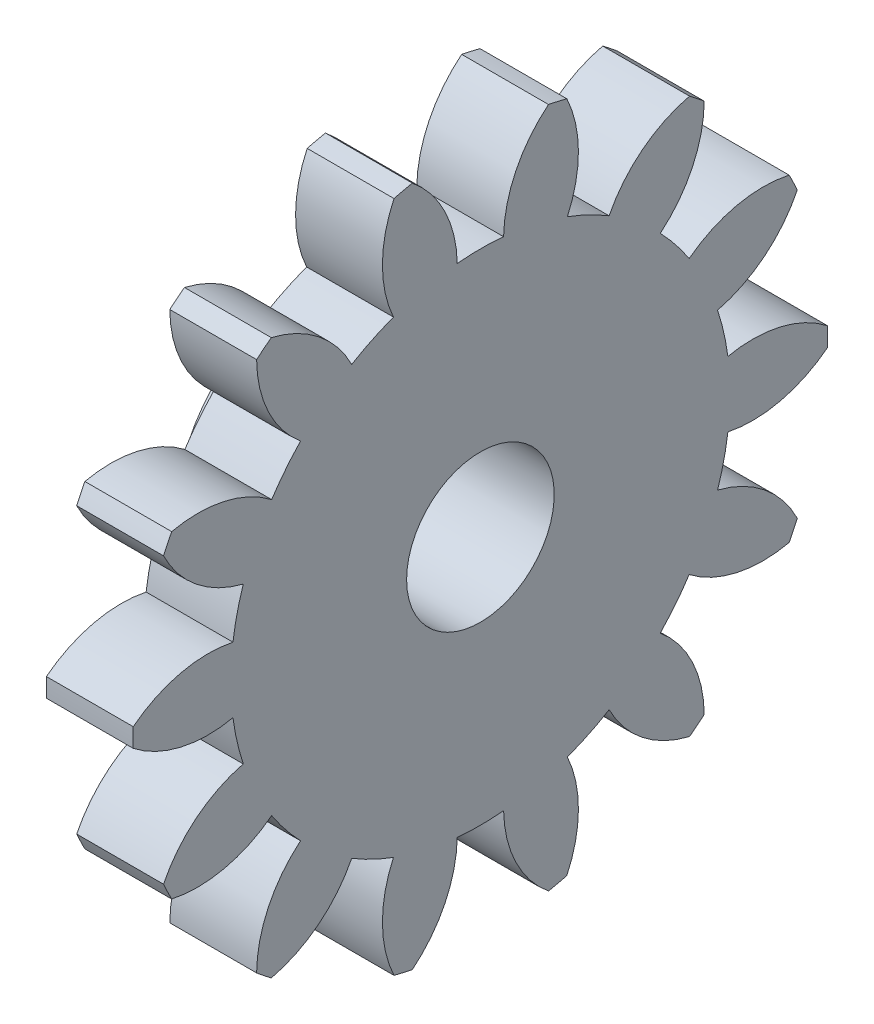
SolidWorks part; units mm, degrees
ref_plane "Plane1" through (0, 0, 0) normal (0, 0, 1) x (1, 0, 0)
ref_plane "Plane2" through (0, 0, 0) normal (0, 1, 0) x (1, 0, 0)
ref_plane "Plane3" through (0, 0, 0) normal (1, 0, 0) x (0, 0, -1)
sketch "HoldingSke" plane through (0, 0, 0) normal (0, 1, 0) x (1, 0, 0)
  line L0 (0, 0) -> (0.1941, -0.0484)
  line L1 (-15, 0) -> (100, 0) construction
  line L2 (0, 0) -> (-2.1039, 2.3779)
  line L3 (0, 0) -> (-11.863, 4.5341)
  line L4 (0, 0) -> (8.3795, 2.0892)
  line L5 (0, 0) -> (-18.7391, -6.9891)
  line L6 (0, 0) -> (-8.2896, -5.593)
  line L7 (-2.1039, 2.3779) -> (2.2011, 21.9091)
  line L8 (-76.2, 54.61) -> (-73.4, 54.61)
  line L9 (-71.009, 38.7566) -> (-53.1078, 45.2721)
  line L10 (-76.2, 71.12) -> (104.1128, 71.12)
  line L11 (0, 0) -> (-10, 0)
  line L12 (-76.2, 101.6) -> (-76.033, 101.6)
  line L13 (24.9733, 27.94) -> (52.9518, 28.4284)
  line L14 (24.9733, 27.94) -> (24.9743, 27.94)
  line L15 (24.9733, 27.94) -> (100.4006, 29.5858)
  line L16 (-63.627, -5) -> (-12.827, -5)
  circle A0 centre (0, 0) radius 8.5
  circle A1 centre (0, 0) radius 15
  circle A2 centre (0, 0) radius 15
  circle A3 centre (0, 0) radius 8.5
  dimension "MHD" = 30
  dimension "Hub_dia" = 30
  dimension "Bore" = 17
  dimension "MBD" = 17
  dimension "Num_teeth" = 14
  dimension "Pitch" = 0.2
  dimension "Overall_len" = 20
  dimension "Show_teeth" = 14
  dimension "Thickness" = 10
  dimension "OAL" = 20.0001
  dimension "T_dim" = 2.8
  dimension "Ap" = 20
  dimension "H" = 19.05
  dimension "Pitch_radius" = 180.3128
  dimension "Width" = 10
  dimension "Backlash" = 0.167
  dimension "Addendum_fac" = 1
  dimension "Dedendum_fac" = 1.25
  dimension "Clearance_fac" = 0.25
  dimension "Dedendum_add" = 0.001
  dimension "Module" = 5
sketch "BasProSke" plane through (0, 0, 0) normal (0, 1, 0) x (1, 0, 0)
  line L0 (-10, 0) -> (60, 0) construction
  line L1 (0, 0) -> (0, 40)
  line L2 (0, 0) -> (10, 0)
  line L3 (10, 0) -> (10, 40)
  line L4 (10, 40) -> (0, 40)
  dimension "Thickness" = 10
  dimension "Diameter" = 80
revolve "Base-Revolve" add sketch "BasProSke" angle 360 about L0
sketch "TooCutSke" plane through (0, 0, 0) normal (1, 0, 0) x (0, 0, -1)
  line L1 (0, 0) -> (0, 107) construction
  line L2 (0, 0) -> (-4.2107, 34.7458) construction
  line L3 (0, 0) -> (-15.4926, 67.8776) construction
  line L4 (-4.2107, 34.7458) -> (-7.7463, 33.9388) construction
  arc A0 (2.669, 28.6248) -> (-2.669, 28.6248) centre (0, 0) ccw
  arc A1 (7.8688, 39.2443) -> (-7.8688, 39.2443) centre (0, 0) ccw
  circle A2 centre (0, 0) radius 35 construction
  circle A3 centre (0, 0) radius 32.8892 construction
  arc A4 (-2.669, 28.6248) -> (-7.8688, 39.2443) centre (-16.6663, 28.3538) ccw
  arc A5 (7.8688, 39.2443) -> (2.669, 28.6248) centre (16.6663, 28.3538) ccw
  dimension "Root_dia" = 57.498
  dimension "Overcut_dia" = 80.0508
  dimension "Pitch_dia" = 70
  dimension "Base_dia" = 65.7785
  dimension "Flank_rad" = 14
  dimension "Half_ang" = 12.857
  dimension "Half_CT" = 3.6265
extrude "ToothCut" cut sketch "TooCutSke" along normal through all
fillet "Breaks" [suppressed] radius 0.1
fillet "RootFillets" [suppressed] radius 1.251
pattern_circular "TeethCuts" count 14 over 360 about axis through (0, 0, 0) along (1, 0, 0) of "ToothCut", "RootFillets", "Breaks"
sketch "HubNeaOneSke" plane through (0, 0, 0) normal (-1, 0, 0) x (0, 0, 1)
  circle A0 centre (0, 0) radius 15
  dimension "Diameter" = 30
extrude "HubNearOne" add sketch "HubNeaOneSke" along normal blind 10.0001
sketch "HubNeaBotSke" plane through (0, 0, 0) normal (-1, 0, 0) x (0, 0, 1)
  circle A0 centre (0, 0) radius 15
  dimension "Diameter" = 30
extrude "HubNearBoth" [suppressed] add sketch "HubNeaBotSke" along normal blind 5
ref_plane "FarPln" through (10, 0, 0) normal (1, 0, 0) x (0, 0, -1)
sketch "HubFarSke" plane through (10, 0, 0) normal (1, 0, 0) x (0, 0, -1)
  circle A0 centre (0, 0) radius 15
  dimension "Diameter" = 30
extrude "HubFar" [suppressed] add sketch "HubFarSke" along normal blind 5
sketch "BorSke" plane through (0, 0, 0) normal (1, 0, 0) x (0, 0, -1)
  circle A0 centre (0, 0) radius 8.5
  dimension "Diameter" = 17
extrude "Bore" cut sketch "BorSke" along normal mid plane 40.0001
sketch "KeySke" plane through (0, 0, 0) normal (1, 0, 0) x (0, 0, -1)
  line L0 (-3, 0) -> (-3, 11.3)
  line L1 (-3, 11.3) -> (3, 11.3)
  line L2 (3, 11.3) -> (3, 0)
  line L3 (0, 0) -> (0, 34) construction
  line L4 (-3, 0) -> (3, 0)
  dimension "Offset" = 11.3
  dimension "Width" = 6
extrude "Keyway" [suppressed] cut sketch "KeySke" along normal mid plane 40.0001
pattern_circular "Keyway2" [suppressed] count 2 every 90 about axis through (-10, 0, 0) along (1, 0, 0)
sketch "Sketch1" plane through (0, 0, 0) normal (0, 1, 0) x (1, 0, 0)
  line L0 (-10.0001, 15) -> (-10.0001, -15) construction
  circle A0 centre (-5.0001, 0) radius 1.75
  dimension "D1" = 5
extrude "Cut-Extrude1" cut sketch "Sketch1" against normal through all both and the other way through all
equation "' \"Module@HoldingSke\" = 6.35"
equation "' \"Num_teeth@HoldingSke\" = 12"
equation "' \"Ap@HoldingSke\" =  20"
equation "' \"Ap@HoldingSke\" = 20"
equation "' \"Width@HoldingSke\" = 0.5 * 25.4"
equation "' \"Hub_dia@HoldingSke\"= 1 * 25.4"
equation "' \"Hub_dia@HoldingSke\" = 1 * 25.4"
equation "' \"Overall_len@HoldingSke\" = 1.0 * 25.4"
equation "' \"Bore@HoldingSke\" = 0.75 * 25.4"
equation "' \"T_dim@HoldingSke\" = 0.1 * 25.4"
equation "' \"Width@KeySke\" = 0.25 * 25.4"
equation "' \"Show_teeth@HoldingSke\" = 13"
equation "' \"Backlash@HoldingSke\" = 0.009 * 25.4"
equation "' \"Addendum_fac@HoldingSke\" = 1.0"
equation "' \"Dedendum_fac@HoldingSke\" = 1.25"
equation "' \"Dedendum_add@HoldingSke\" = 0.00005 * 25.4"
equation "' \"Clearance_fac@HoldingSke\" = 0.25"
equation "\"Pitch@HoldingSke\" = 1 / \"Module@HoldingSke\""
equation "\"Overcut_dia@TooCutSke\" = (\"Num_teeth@HoldingSke\" + 2 * \"Addendum_fac@HoldingSke\") / \"Pitch@HoldingSke\" + 0.002 * 25.4"
equation "\"Pitch_dia@TooCutSke\" = \"Num_teeth@HoldingSke\" / \"Pitch@HoldingSke\""
equation "\"Base_dia@TooCutSke\" = \"Num_teeth@HoldingSke\" / \"Pitch@HoldingSke\" * cos((\"Ap@HoldingSke\"  * 3.14159265 / 180))"
equation "\"Root_dia@TooCutSke\" = (\"Num_teeth@HoldingSke\" + 2) / \"Pitch@HoldingSke\" - 2 * (\"Addendum_fac@HoldingSke\" + \"Dedendum_fac@HoldingSke\") / \"Pitch@HoldingSke\" - \"Dedendum_add@HoldingSke\" * 2"
equation "\"Half_ang@TooCutSke\" = 180 / \"Num_teeth@HoldingSke\""
equation "\"Half_CT@TooCutSke\" = \"Num_teeth@HoldingSke\" / \"Pitch@HoldingSke\" * sin((3.14159265 / 2 / \"Num_teeth@HoldingSke\")) / 2 - 7 * \"Backlash@HoldingSke\" / 4"
equation "\"Flank_rad@TooCutSke\" = \"Num_teeth@HoldingSke\" / \"Pitch@HoldingSke\" / 5"
equation "\"Radius@RootFillets\" = \"Clearance_fac@HoldingSke\" / \"Pitch@HoldingSke\" + \"Dedendum_add@HoldingSke\""
equation "\"Break_rad@Breaks\" = 0.02 / \"Pitch@HoldingSke\""
equation "\"Thickness@HoldingSke\" = \"Width@HoldingSke\""
equation "\"OAL@HoldingSke\" = \"Thickness@HoldingSke\""
equation "\"MHD@HoldingSke\" = (\"Num_teeth@HoldingSke\" + 2) / \"Pitch@HoldingSke\" - 2 * (\"Addendum_fac@HoldingSke\" + \"Dedendum_fac@HoldingSke\")  / \"Pitch@HoldingSke\" - \"Dedendum_add@HoldingSke\" * 2"
equation "\"MBD@HoldingSke\" = (\"Num_teeth@HoldingSke\" + 2) / \"Pitch@HoldingSke\" - 2 * (\"Addendum_fac@HoldingSke\" + \"Dedendum_fac@HoldingSke\")  / \"Pitch@HoldingSke\" - \"Dedendum_add@HoldingSke\" * 2 - 0.002 * 25.4"
equation "\"MHD@HoldingSke\" = ((sgn( \"MHD@HoldingSke\" - \"Hub_dia@HoldingSke\" )-1)*( \"MHD@HoldingSke\" - \"Hub_dia@HoldingSke\" ))/-2+ \"Hub_dia@HoldingSke\""
equation "\"MBD@HoldingSke\" = ((sgn( \"MBD@HoldingSke\" - \"Bore@HoldingSke\" )-1)*( \"MBD@HoldingSke\" - \"Bore@HoldingSke\" ))/-2+ \"Bore@HoldingSke\""
equation "\"OAL@HoldingSke\" = ((sgn( \"OAL@HoldingSke\" - \"Overall_len@HoldingSke\" )+1)*( \"OAL@HoldingSke\" - \"Overall_len@HoldingSke\" ))/2 + \"Overall_len@HoldingSke\" + 0.000002 * 25.4"
equation "\"Num_teeth@TeethCuts\" = int( \"Show_teeth@HoldingSke\" ) + 1"
equation "\"Num_teeth@TeethCuts\" = ((sgn( \"Num_teeth@TeethCuts\" - \"Num_teeth@HoldingSke\" )-1)*( \"Num_teeth@TeethCuts\" - \"Num_teeth@HoldingSke\" ))/-2+ \"Num_teeth@HoldingSke\""
equation "\"Num_teeth@TeethCuts\" = ((sgn( \"Num_teeth@TeethCuts\" - 2.0)+1)*( \"Num_teeth@TeethCuts\" - 2.0))/2 +2.0"
equation "\"Angle@TeethCuts\" = 360.0 / \"Num_teeth@HoldingSke\""
equation "\"Diameter@BasProSke\" = (\"Num_teeth@HoldingSke\" + 2 * \"Addendum_fac@HoldingSke\") / \"Pitch@HoldingSke\""
equation "\"Thickness@BasProSke\"  = \"Thickness@HoldingSke\""
equation "' \"Fillet_rad@BasProSke\" =  \"Thickness@HoldingSke\" * 0.05"
equation "' \"Fillet_rad@BasProSke\" = \"Thickness@HoldingSke\" * 0.05"
equation "\"MHD@HoldingSke\" = ((sgn( \"MHD@HoldingSke\" - \"Root_dia@TooCutSke\" )-1)*( \"MHD@HoldingSke\" - \"Root_dia@TooCutSke\" ))/-2+ \"Root_dia@TooCutSke\""
equation "\"Diameter@HubNeaOneSke\" = \"MHD@HoldingSke\""
equation "\"Length@HubNearOne\" = \"OAL@HoldingSke\" - \"Thickness@BasProSke\""
equation "\"Diameter@HubNeaBotSke\" = \"MHD@HoldingSke\""
equation "\"Length@HubNearBoth\" = ( \"OAL@HoldingSke\" - \"Thickness@BasProSke\" ) / 2.0"
equation "\"Thickness@FarPln\" = \"Thickness@BasProSke\""
equation "\"Diameter@HubFarSke\" = \"MHD@HoldingSke\""
equation "\"Length@HubFar\" = ( \"OAL@HoldingSke\" - \"Thickness@BasProSke\" ) / 2.0"
equation "\"Diameter@BorSke\" = \"MBD@HoldingSke\""
equation "\"D1@Bore\" = \"OAL@HoldingSke\" * 2.0"
equation "\"D1@Keyway\" = \"OAL@HoldingSke\" * 2.0"
equation "\"Offset@KeySke\" = \"T_dim@HoldingSke\" + \"MBD@HoldingSke\" / 2.0"
